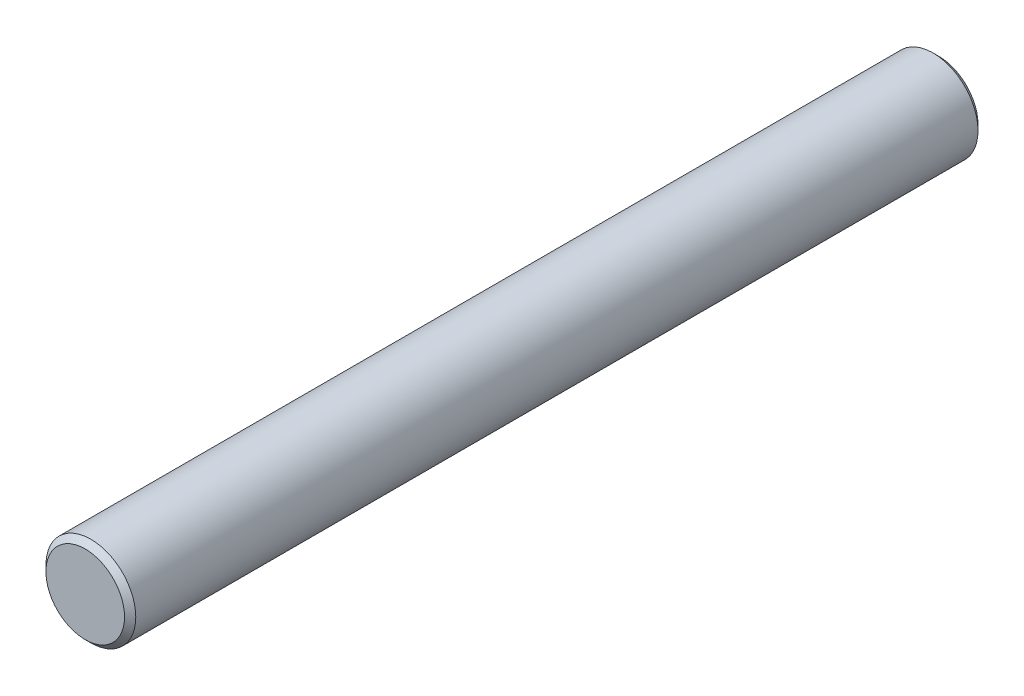
SolidWorks part; units mm, degrees
ref_plane "Alzado" through (0, 0, 0) normal (0, 0, 1) x (1, 0, 0)
ref_plane "Planta" through (0, 0, 0) normal (0, 1, 0) x (1, 0, 0)
ref_plane "Vista lateral" through (0, 0, 0) normal (1, 0, 0) x (0, 0, -1)
sketch "Croquis1" plane through (0, 0, 0) normal (0, 0, 1) x (1, 0, 0)
  circle A0 centre (0, 0) radius 4
  dimension "D1" = 8
extrude "Saliente-Extruir1" add sketch "Croquis1" against normal blind 76
chamfer "Chaflán1" distance 0.5 angle 45 2 edges at (4, 0, -76) (4, 0, 0)
